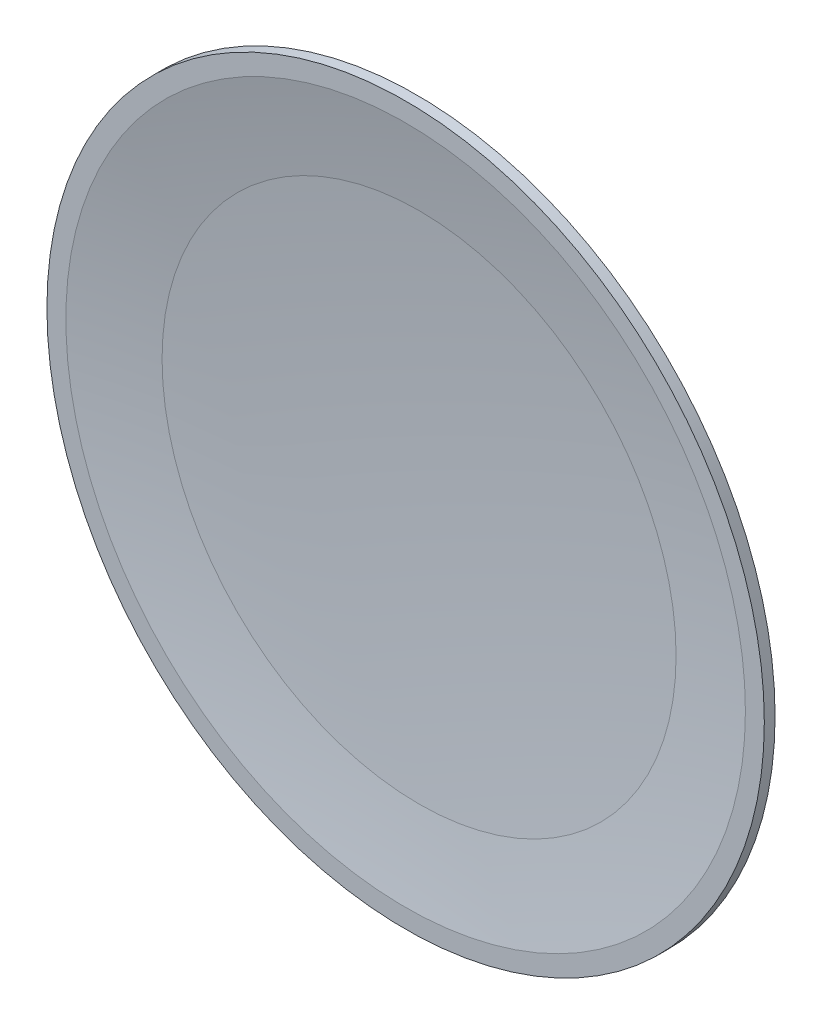
SolidWorks part; units mm, degrees
ref_plane "前视基准面" through (0, 0, 0) normal (0, 0, 1) x (1, 0, 0)
ref_plane "上视基准面" through (0, 0, 0) normal (0, 1, 0) x (1, 0, 0)
ref_plane "右视基准面" through (0, 0, 0) normal (1, 0, 0) x (0, 0, -1)
sketch "草图1" plane through (0, 0, 0) normal (0, 1, 0) x (1, 0, 0)
  line L0 (0, 22.1284) -> (0, -12.8657) construction
  line L1 (4.75, 37.6425) -> (5, 37.6425)
  line L2 (4.7362, 37.4925) -> (5, 37.4925)
  line L3 (0, 38) -> (0, 37.85)
  line L4 (5, 37.6425) -> (5, 37.4925)
  arc A0 (0, 38) -> (3.6, 37.8291) centre (0, 0) cw
  arc A1 (3.6, 37.8291) -> (4.75, 37.6425) centre (0, 12) cw
  arc A2 (0, 37.85) -> (3.5825, 37.6801) centre (0, 0) cw
  arc A3 (3.5825, 37.6801) -> (4.7362, 37.4925) centre (0, 12) cw
  dimension "D1" = 3.6
  dimension "D2" = 38
  dimension "D3" = 12
  dimension "D4" = 4.75
  dimension "D5" = 5
  dimension "D6" = 0.15
revolve "旋转5" add sketch "草图1" angle 360 about L0
sketch "草图2" plane through (0, 0, -37.4925) normal (0, 0, 1) x (1, 0, 0)
  point P0 (0, 0)
